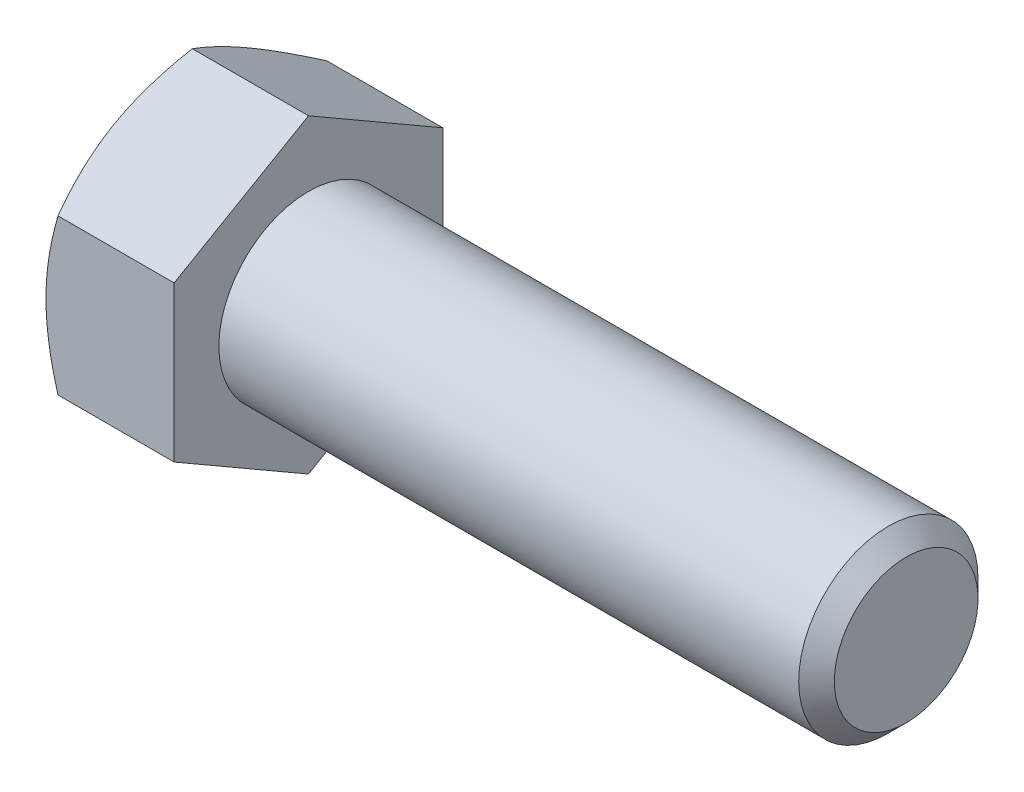
SolidWorks part; units mm, degrees
extrude "BaseHead" add sketch "Sketch1" along normal blind 6.8072
sketch "Sketch1" plane through (0, 0, 0) normal (1, 0, 0) x (0, 0, -1)
  line L0 (7.1374, 4.1208) -> (7.1374, -4.1208)
  line L1 (-7.1374, 4.1208) -> (-7.1374, -4.1208)
  line L2 (7.1374, -4.1208) -> (0, -8.2416)
  line L3 (0, -8.2416) -> (-7.1374, -4.1208)
  line L4 (7.1374, 4.1208) -> (0, 8.2416)
  line L5 (0, 8.2416) -> (-7.1374, 4.1208)
  dimension "D2" = 120
ref_plane "Plane1" through (0, 0, 0) normal (0, 0, 1) x (1, 0, 0)
ref_plane "Plane2" through (0, 0, 0) normal (0, 1, 0) x (1, 0, 0)
ref_plane "Plane3" through (0, 0, 0) normal (1, 0, 0) x (0, 0, -1)
sketch "BodySke" plane through (0, 0, 0) normal (0, 0, 1) x (1, 0, 0)
  line L0 (0, 4.1208) -> (0, -4.1208) construction
  line L1 (0, 0) -> (38.5572, 0)
  line L2 (0, 0) -> (0, 4.7625)
  line L3 (0, 4.7625) -> (37.6111, 4.7625)
  line L4 (38.5572, 0) -> (38.5572, 3.8163)
  line L5 (6.8072, 8.2416) -> (6.8072, 4.1208) construction
  line L6 (38.5572, 3.8163) -> (37.6111, 4.7625)
  line L7 (0, 0) -> (96.52, 0) construction
  line L8 (38.5572, -3.8163) -> (37.6111, -4.7625) construction
  line L9 (0, -4.7625) -> (37.6111, -4.7625) construction
  line L10 (8.3947, 15.24) -> (8.3947, -2.54) construction
  line L11 (13.1572, 15.24) -> (13.1572, -2.54) construction
  line L12 (6.8072, 4.1208) -> (6.8072, -4.1208) construction
revolve "BaseBody" add sketch "BodySke" angle 360 about L7
cosmetic thread "ThreadCosmetic" [suppressed] parameters "Thread_length"=25.4, "Thread_minor"=7.6327
sketch "Sketch3" plane through (0, 0, 0) normal (0, 0, 1) x (1, 0, 0)
  line L0 (0, 7.1374) -> (4.3037, 14.5916)
  line L1 (0, 8.2416) -> (0, 4.1208) construction
  line L2 (4.3037, 14.5916) -> (4.3037, 20.9416)
  line L3 (4.3037, 20.9416) -> (-12.7, 20.9416)
  line L4 (-12.7, 20.9416) -> (-12.7, 7.1374)
  line L5 (-12.7, 7.1374) -> (0, 7.1374)
  line L6 (0, 0) -> (99.06, 0) construction
  line L7 (6.8072, 8.2416) -> (0, 8.2416) construction
  dimension "D2" = 6.35
  dimension "D3" = 12.7
  dimension "D4" = 6.35
  dimension "Head_ch_ang" = 30
revolve "HeadChamfer" cut sketch "Sketch3" angle 360 about L6
fillet "HeadFillet" [suppressed] radius 0.762
sketch "ThdSchSke" plane through (0, 0, 0) normal (0, 0, 1) x (1, 0, 0)
  line L0 (13.1572, -3.8163) -> (12.4947, -4.7625)
  line L1 (13.1572, -3.8163) -> (13.8197, -4.7625)
  line L2 (13.8197, -4.7625) -> (13.8197, -5.9531)
  line L3 (-3.175, 0) -> (5.1513, 0) construction
  line L5 (13.8197, -5.9531) -> (12.4947, -5.9531)
  line L6 (12.4947, -5.9531) -> (12.4947, -4.7625)
revolve "ThreadSchematic" [suppressed] cut sketch "ThdSchSke" angle 360 about L3
pattern_linear "ThdSchPat" [suppressed]
equation "\"D3@Sketch1\" = \"Width_flats@Sketch1\" / 2"
equation "\"D4@Sketch1\" = \"D3@Sketch1\""
equation "\"D5@Sketch1\" = \"D4@Sketch1\""
equation "\"Thread_minor@ThreadCosmetic\" = \"Minor_dia@BodySke\""
equation "\"D1@Sketch3\" = \"Width_flats@Sketch1\" / 2"
equation "\"Thread_length@ThreadCosmetic\" = ((sgn( (\"Length@BodySke\" - \"Advance@BodySke\" ) - \"Thread_nom@BodySke\" )-1)*( (\"Length@BodySke\" - \"Advance@BodySke\" ) - \"Thread_nom@BodySke\" ))/-2+ \"Thread_nom@BodySke\""
equation "\"Thread_minor@ThdSchSke\" = \"Minor_dia@BodySke\""
equation "\"Diameter@ThdSchSke\" = \"Diameter@BodySke\""
equation "\"Overcut@ThdSchSke\" = \"Diameter@BodySke\" * 1.25"
equation "\"Start@ThdSchSke\" = \"Head_ht@BaseHead\" + \"Length@BodySke\" - \"Thread_length@ThreadCosmetic\"  '---Non-countersunk---"
equation "\"Num_threads@ThdSchPat\" = int( \"Thread_length@ThreadCosmetic\" / \"Advance@BodySke\" + 0.999 )  + 1"
equation "\"Advance@ThdSchPat\" = \"Thread_length@ThreadCosmetic\" /  (\"Num_threads@ThdSchPat\" - 1) 'relax it"
equation "\"Num_threads@ThdSchPat\" = \"Num_threads@ThdSchPat\" - sgn( \"Num_threads@ThdSchPat\" - 1) '---chamfered tips only---"
